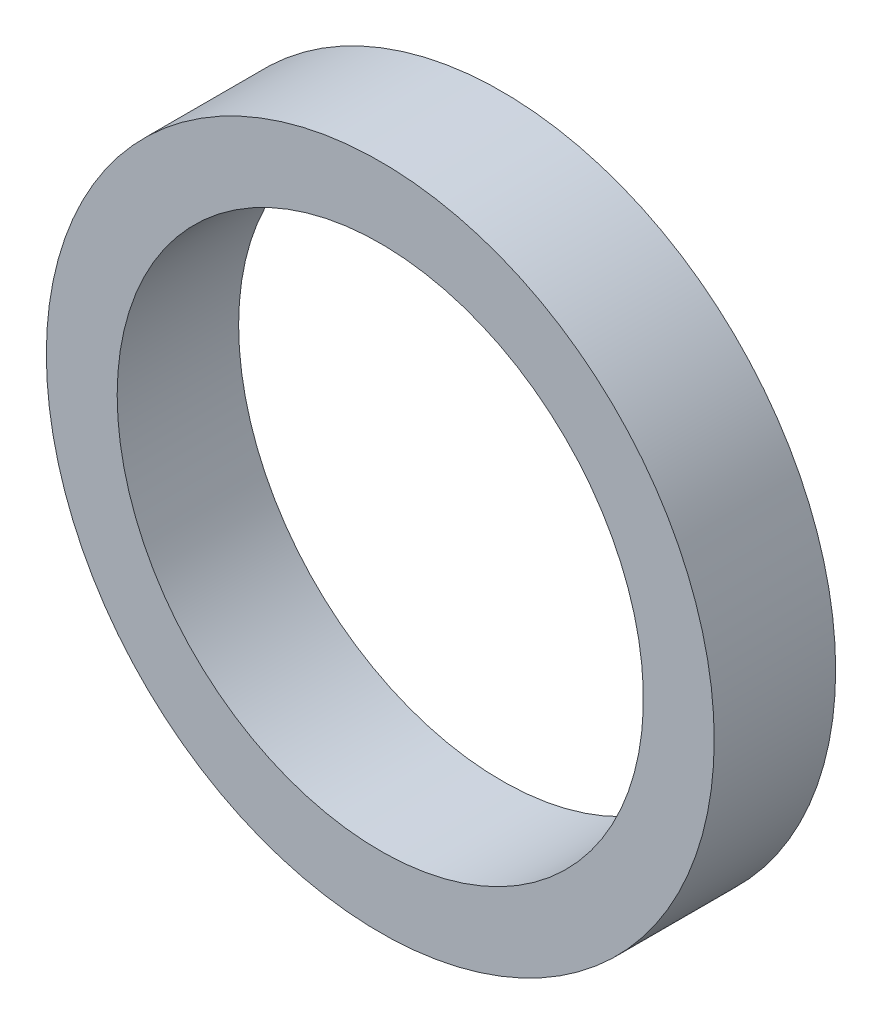
SolidWorks part; units mm, degrees
ref_plane "Front Plane" through (0, 0, 0) normal (0, 0, 1) x (1, 0, 0)
ref_plane "Top Plane" through (0, 0, 0) normal (0, 1, 0) x (1, 0, 0)
ref_plane "Right Plane" through (0, 0, 0) normal (1, 0, 0) x (0, 0, -1)
sketch "Sketch1" plane through (0, 0, 0) normal (0, 1, 0) x (1, 0, 0)
  line L0 (-91.9441, 0) -> (102.1149, 0) construction
  line L1 (0, 72.6196) -> (0, -82.7904) construction
  line L3 (-82.5, 15) -> (-65, 15)
  line L4 (-82.5, 15) -> (-82.5, -15)
  line L5 (-82.5, -15) -> (-65, -15)
  line L6 (-65, 15) -> (-65, -15)
  point P5 (-65, 0)
  point P10 (-65, 0)
  dimension "D1" = 65
  dimension "D2" = 30
  dimension "D3" = 82.5
revolve "Revolve2" add sketch "Sketch1" angle 360 about L1
